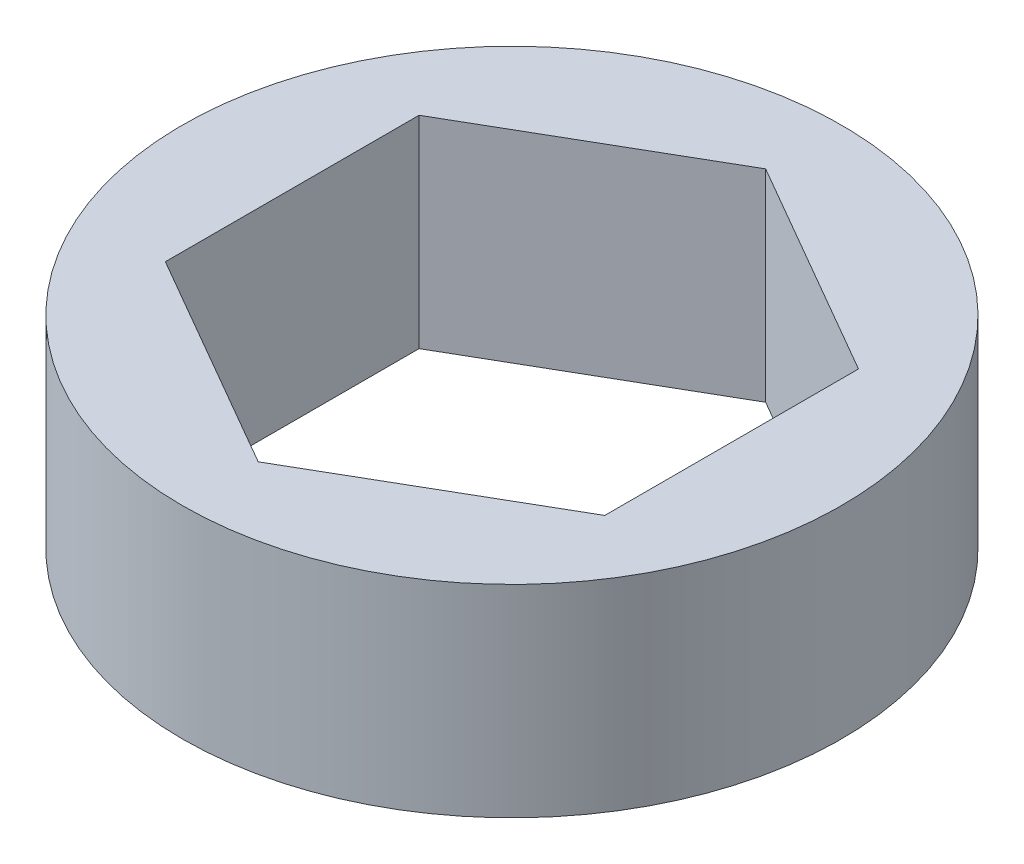
SolidWorks part; units mm, degrees
ref_plane "Front Plane" through (0, 0, 0) normal (0, 0, 1) x (1, 0, 0)
ref_plane "Top Plane" through (0, 0, 0) normal (0, 1, 0) x (1, 0, 0)
ref_plane "Right Plane" through (0, 0, 0) normal (1, 0, 0) x (0, 0, -1)
sketch "Sketch1" plane through (0, 0, 0) normal (0, 1, 0) x (1, 0, 0)
  line L1 (0, 7.3323) -> (-6.35, 3.6662)
  line L2 (-6.35, 3.6662) -> (-6.35, -3.6662)
  line L3 (-6.35, -3.6662) -> (0, -7.3323)
  line L4 (0, -7.3323) -> (6.35, -3.6662)
  line L5 (6.35, -3.6662) -> (6.35, 3.6662)
  line L6 (6.35, 3.6662) -> (0, 7.3323)
  circle A0 centre (0, 0) radius 6.35 construction
  circle A1 centre (0, 0) radius 9.525
  dimension "D1" = 12.7
  dimension "D2" = 19.05
extrude "Boss-Extrude1" add sketch "Sketch1" along normal blind 5.842
